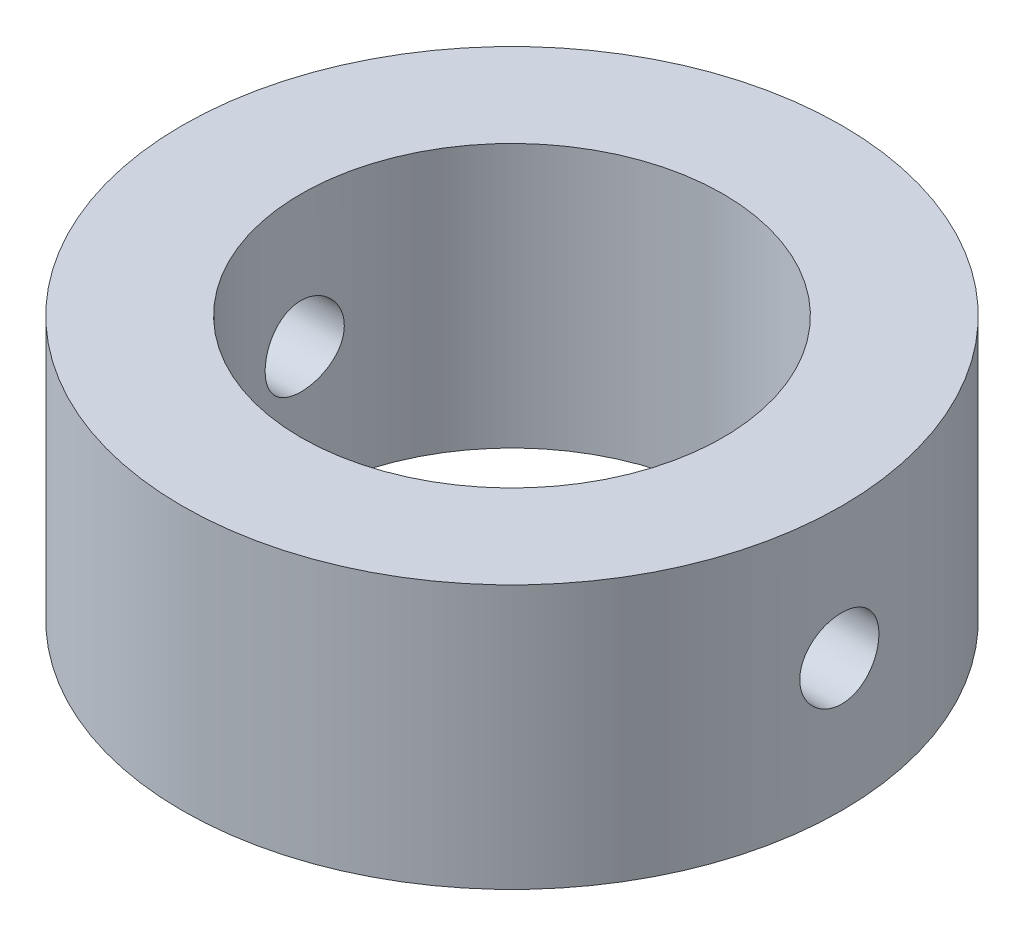
SolidWorks part; units mm, degrees
material "AISI 4130 Steel, normalized at 870C"
ref_plane "Front Plane" through (0, 0, 0) normal (0, 0, 1) x (1, 0, 0)
ref_plane "Top Plane" through (0, 0, 0) normal (0, 1, 0) x (1, 0, 0)
ref_plane "Right Plane" through (0, 0, 0) normal (1, 0, 0) x (0, 0, -1)
sketch "Sketch1" plane through (0, 0, 0) normal (0, 1, 0) x (1, 0, 0)
  circle A0 centre (0, 0) radius 12.5
  circle A1 centre (0, 0) radius 8
extrude "Boss-Extrude1" add sketch "Sketch1" along normal blind 10
sketch "Sketch2" plane through (0, 10, 0) normal (0, 1, 0) x (1, 0, 0)
  line L0 (0, 0) -> (-12.5, 0) construction
  circle A0 centre (0, 0) radius 12.5 construction
ref_plane "Plane1" through (-12.5, 0, 0) normal (-1, 0, 0) x (0, 0, 1)
sketch "Sketch3" plane through (-12.5, 0, 0) normal (-1, 0, 0) x (0, 0, 1)
  line L0 (8, 10) -> (-8, 10) construction
  line L1 (-12.5, 10) -> (-12.5, 0) construction
  circle A0 centre (0, 5) radius 1.5
  dimension "D1" = 5
  dimension "D2" = 12.5
extrude "Cut-Extrude1" cut sketch "Sketch3" against normal through all
scale "Escala1" scale about centroid uniform scaling yes scale factor 0.5
